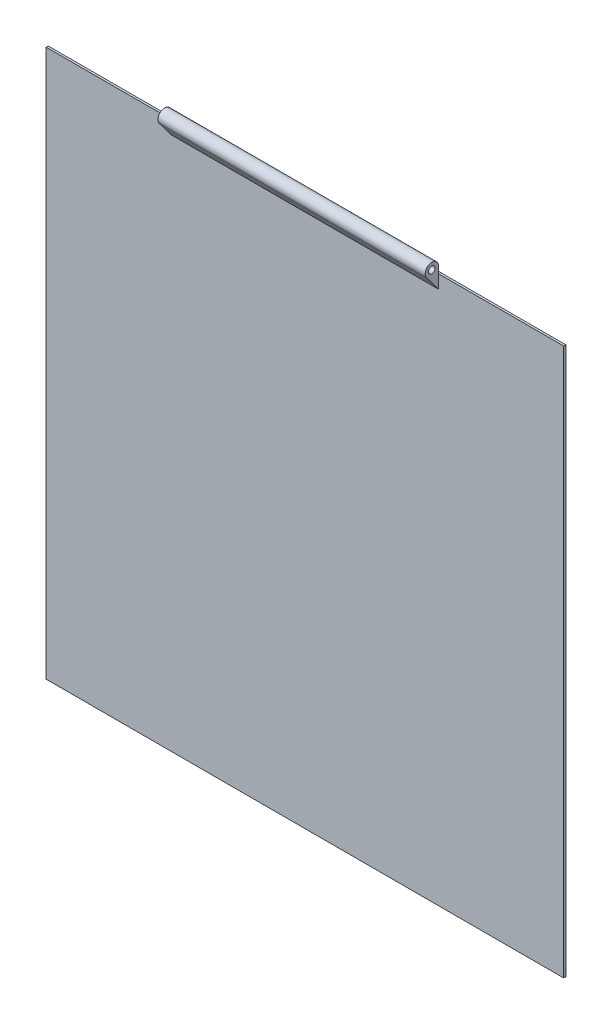
SolidWorks part; units mm, degrees
ref_plane "Front Plane" through (0, 0, 0) normal (0, 0, 1) x (1, 0, 0)
ref_plane "Top Plane" through (0, 0, 0) normal (0, 1, 0) x (1, 0, 0)
ref_plane "Right Plane" through (0, 0, 0) normal (1, 0, 0) x (0, 0, -1)
sketch "Sketch1" plane through (0, 0, 0) normal (0, 0, 1) x (1, 0, 0)
  line L1 (-193.65, 0) -> (193.65, 0)
  line L2 (-193.65, 0) -> (-193.65, -409.62)
  line L3 (-193.65, -409.62) -> (193.65, -409.62)
  line L4 (193.65, 0) -> (193.65, -409.62)
  point P5 (0, 0)
  dimension "D1" = 387.3
  dimension "D2" = 409.62
extrude "Boss-Extrude1" add sketch "Sketch1" along normal blind 1.5875
sketch "Sketch2" plane through (0, 0, 0) normal (1, 0, 0) x (0, 0, -1)
  line L0 (-1.5875, -10) -> (-1.5875, 10)
  line L1 (-1.5875, -409.62) -> (-1.5875, 0) construction
  line L2 (-1.5875, 10) -> (-6.5875, 10)
  line L3 (-10.5875, 2) -> (-1.5875, -10)
  circle A2 centre (-9.4571, 5.6462) radius 0.0001
  circle A4 centre (-6.5875, 5) radius 2.5
  circle A5 centre (-6.5875, 5) radius 5
  dimension "D3" = 5
  dimension "D4" = 5
  dimension "D1" = 10
  dimension "D2" = 10
  dimension "D5" = 5
extrude "Boss-Extrude3" add sketch "Sketch2" against normal mid plane 200 contours A5 L3 L0 | A5 A2 A4
